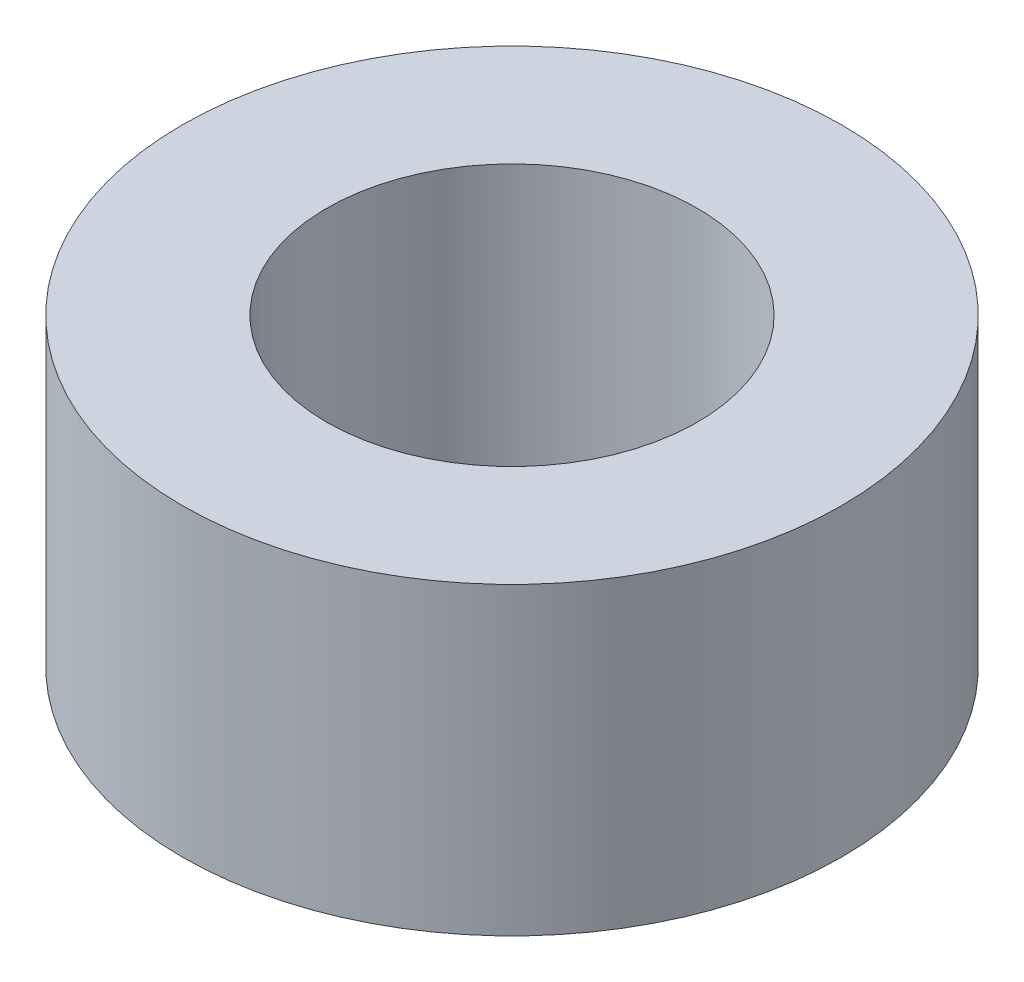
SolidWorks part; units mm, degrees
ref_plane "Front Plane" through (0, 0, 0) normal (0, 0, 1) x (1, 0, 0)
ref_plane "Top Plane" through (0, 0, 0) normal (0, 1, 0) x (1, 0, 0)
ref_plane "Right Plane" through (0, 0, 0) normal (1, 0, 0) x (0, 0, -1)
sketch "Sketch1" plane through (0, 0, 0) normal (0, 1, 0) x (1, 0, 0)
  circle A0 centre (0, 0) radius 14.23
extrude "Boss-Extrude1" add sketch "Sketch1" along normal blind 13.14
sketch "Sketch2" plane through (0, 13.14, 0) normal (0, 1, 0) x (1, 0, 0)
  circle A0 centre (0, 0) radius 8
extrude "Cut-Extrude1" cut sketch "Sketch2" against normal blind 13.14
